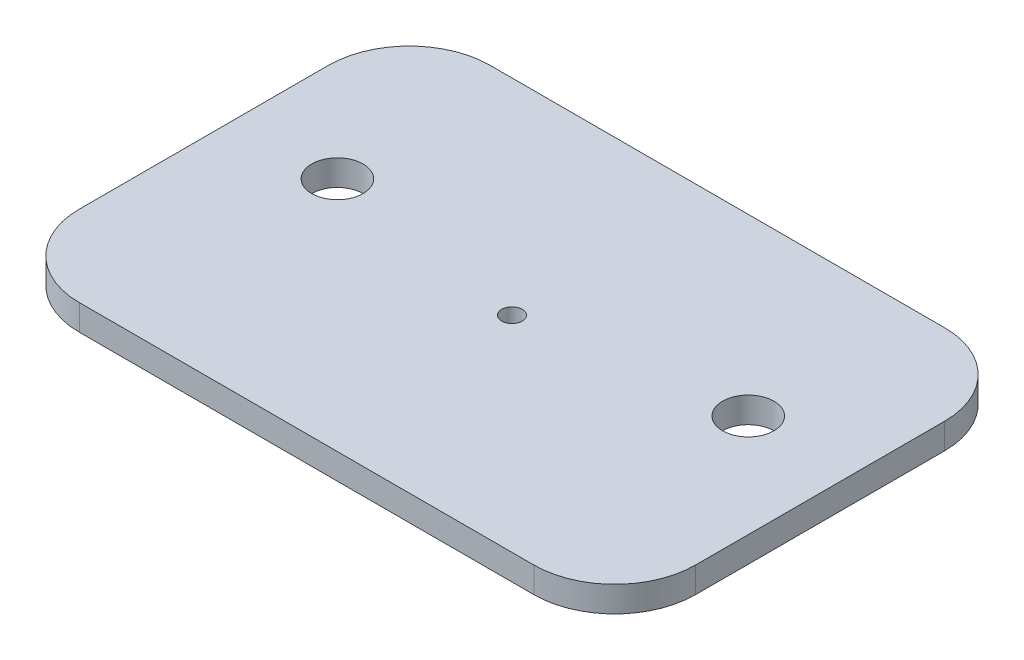
SolidWorks part; units mm, degrees
ref_plane "Front Plane" through (0, 0, 0) normal (0, 0, 1) x (1, 0, 0)
ref_plane "Top Plane" through (0, 0, 0) normal (0, 1, 0) x (1, 0, 0)
ref_plane "Right Plane" through (0, 0, 0) normal (1, 0, 0) x (0, 0, -1)
sketch "Sketch1" plane through (0, 0, 0) normal (0, 1, 0) x (1, 0, 0)
  line L1 (-38.1, -25.4) -> (38.1, -25.4)
  line L2 (-38.1, -25.4) -> (-38.1, 25.4)
  line L3 (-38.1, 25.4) -> (38.1, 25.4)
  line L4 (38.1, -25.4) -> (38.1, 25.4)
  line L5 (-38.1, -25.4) -> (38.1, 25.4) construction
  line L6 (-38.1, 25.4) -> (38.1, -25.4) construction
  circle A0 centre (-25.4, 3.81) radius 3.175
  circle A1 centre (25.4, 3.81) radius 3.175
  circle A2 centre (0, 0) radius 1.27
  point P0 (0, 0)
  dimension "D3" = 6.35
  dimension "D5" = 50.8
  dimension "D6" = 12.7
  dimension "D7" = 2.54
  dimension "D1" = 76.2
  dimension "D2" = 50.8
  dimension "D4" = 21.59
extrude "Boss-Extrude1" add sketch "Sketch1" along normal blind 3.175
fillet "Fillet1" radius 10 4 edges at (38.1, 1.5875, 25.4) (-38.1, 1.5875, 25.4) (-38.1, 1.5875, -25.4) (38.1, 1.5875, -25.4)
